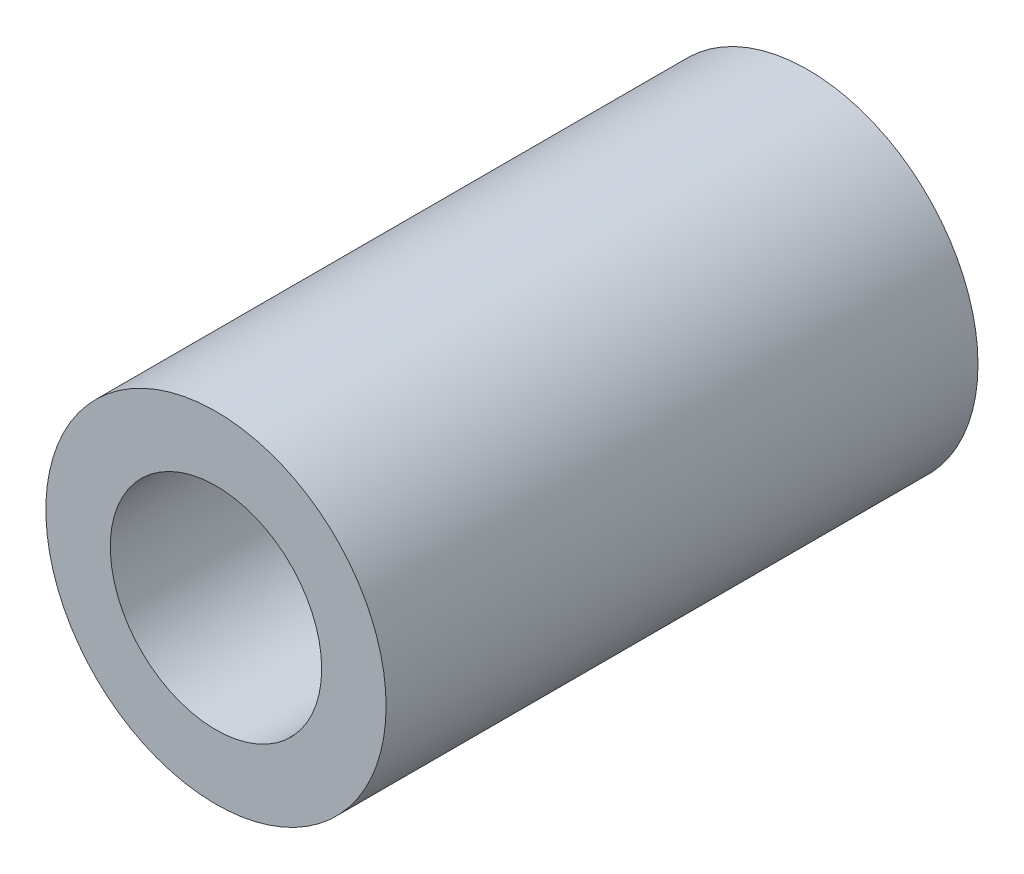
SolidWorks part; units mm, degrees
ref_plane "Front Plane" through (0, 0, 0) normal (0, 0, 1) x (1, 0, 0)
ref_plane "Top Plane" through (0, 0, 0) normal (0, 1, 0) x (1, 0, 0)
ref_plane "Right Plane" through (0, 0, 0) normal (1, 0, 0) x (0, 0, -1)
sketch "Sketch1" plane through (0, 0, 0) normal (0, 0, 1) x (1, 0, 0)
  circle A0 centre (0, 0) radius 6.3881
  circle A1 centre (0, 0) radius 3.9688
  dimension "OD" = 12.7762
  dimension "ID" = 7.9375
sketch "Sketch2" plane through (0, 0, 0) normal (1, 0, 0) x (0, 0, -1)
  line L2 (11.1125, 0) -> (-11.1125, 0) construction
  line L4 (-11.1125, -6.3881) -> (-11.1125, 6.3881) construction
  line L5 (-11.1125, -3.9688) -> (11.1125, -3.9687)
  line L6 (11.1125, 3.9688) -> (-11.1125, 3.9688)
  line L7 (11.1125, -6.3881) -> (11.1125, 6.3881) construction
  line L8 (-11.1125, 6.3881) -> (11.1125, 6.3881) construction
  line L9 (-11.1125, -6.3881) -> (11.1125, -6.3881) construction
  line L10 (0, 6.3881) -> (0, -6.3881) construction
  line L11 (0, 3.9688) -> (0, -3.9688) construction
  point P4 (0, -3.9688)
  point P7 (0, 3.9688)
  point P8 (0, 0)
  point P12 (-11.1125, 0)
  point P15 (11.1125, 0)
  point P16 (0, -6.3881)
  point P17 (0, 6.3881)
  dimension "Length" = 22.225
sketch "Sketch5" plane through (0, 0, 0) normal (0, 0, 1) x (1, 0, 0)
  circle A1 centre (0, 0) radius 3.9688
  circle A2 centre (0, 0) radius 3.9688
  circle A3 centre (0, 0) radius 6.3881
  circle A4 centre (0, 0) radius 6.3881
  dimension "D1" = 0
  dimension "D2" = 0
extrude "Boss-Extrude1" add sketch "Sketch5" along normal mid plane 22.225
equation "\"D1@Boss-Extrude1\" = \"Length@Sketch2\""
